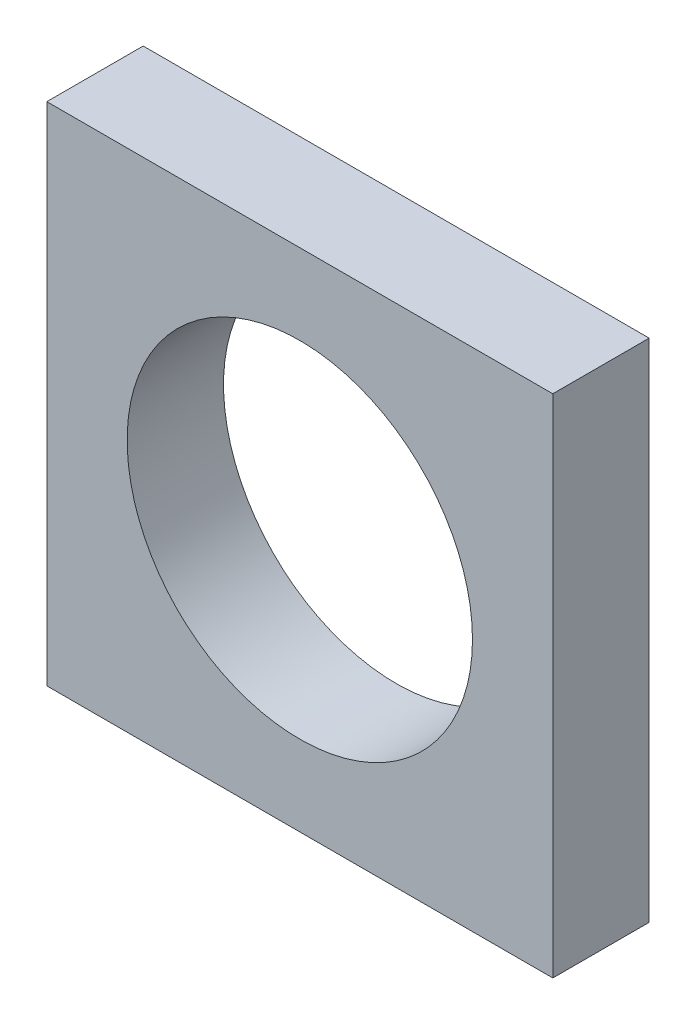
SolidWorks part; units mm, degrees
ref_plane "Plan de face" through (0, 0, 0) normal (0, 0, 1) x (1, 0, 0)
ref_plane "Plan de dessus" through (0, 0, 0) normal (0, 1, 0) x (1, 0, 0)
ref_plane "Plan de droite" through (0, 0, 0) normal (1, 0, 0) x (0, 0, -1)
sketch "Esquisse1" plane through (0, 0, 0) normal (0, 0, 1) x (1, 0, 0)
  line L1 (0, 0) -> (31.5, 0)
  line L2 (0, 0) -> (0, 31.5)
  line L3 (0, 31.5) -> (31.5, 31.5)
  line L4 (31.5, 0) -> (31.5, 31.5)
  circle A0 centre (15.75, 15.75) radius 10.75
  dimension "D1" = 21.5
  dimension "D2" = 15.75
  dimension "D3" = 15.75
  dimension "D5" = 15.75
  dimension "D4" = 15.75
extrude "Boss.-Extru.1" add sketch "Esquisse1" along normal blind 6
